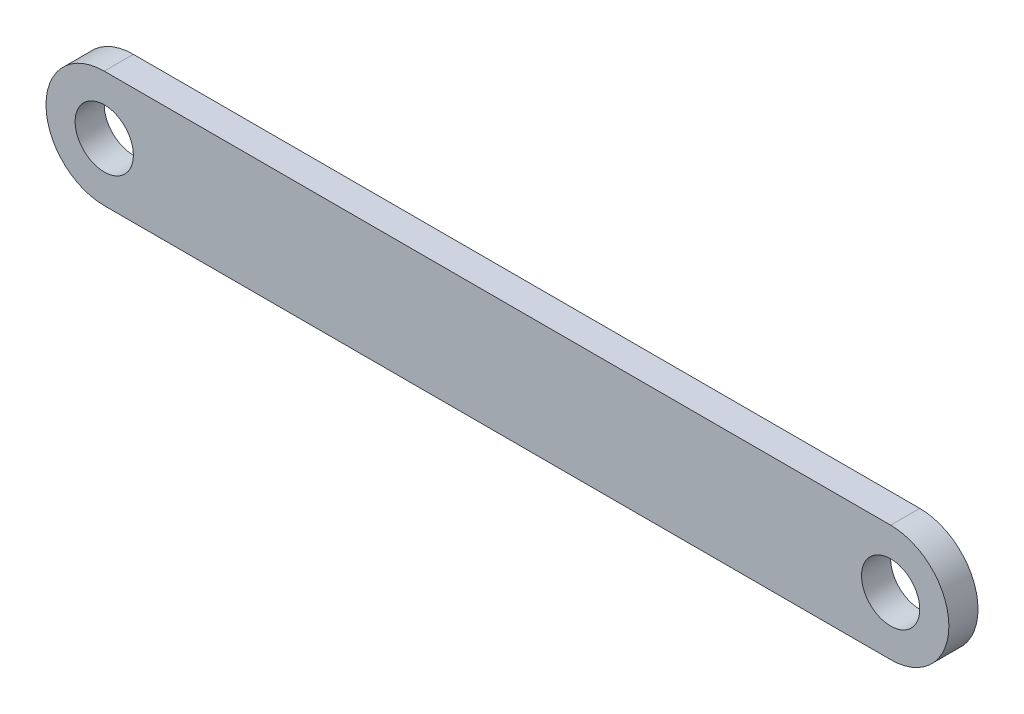
SolidWorks part; units mm, degrees
ref_plane "Alzado" through (0, 0, 0) normal (0, 0, 1) x (1, 0, 0)
ref_plane "Planta" through (0, 0, 0) normal (0, 1, 0) x (1, 0, 0)
ref_plane "Vista lateral" through (0, 0, 0) normal (1, 0, 0) x (0, 0, -1)
sketch "Croquis1" plane through (0, 0, 0) normal (0, 0, 1) x (1, 0, 0)
  line L0 (-67.5, 0) -> (67.5, 0) construction
  line L1 (-67.5, 10) -> (67.5, 10)
  line L2 (-67.5, -10) -> (67.5, -10)
  arc A0 (-67.5, 10) -> (-67.5, -10) centre (-67.5, 0) ccw
  arc A1 (67.5, -10) -> (67.5, 10) centre (67.5, 0) ccw
  circle A2 centre (67.5, 0) radius 5
  circle A3 centre (-67.5, 0) radius 5
  point P2 (0, 0)
  dimension "D2" = 10
  dimension "D1" = 135
  dimension "D3" = 20
extrude "Saliente-Extruir1" add sketch "Croquis1" along normal blind 5
